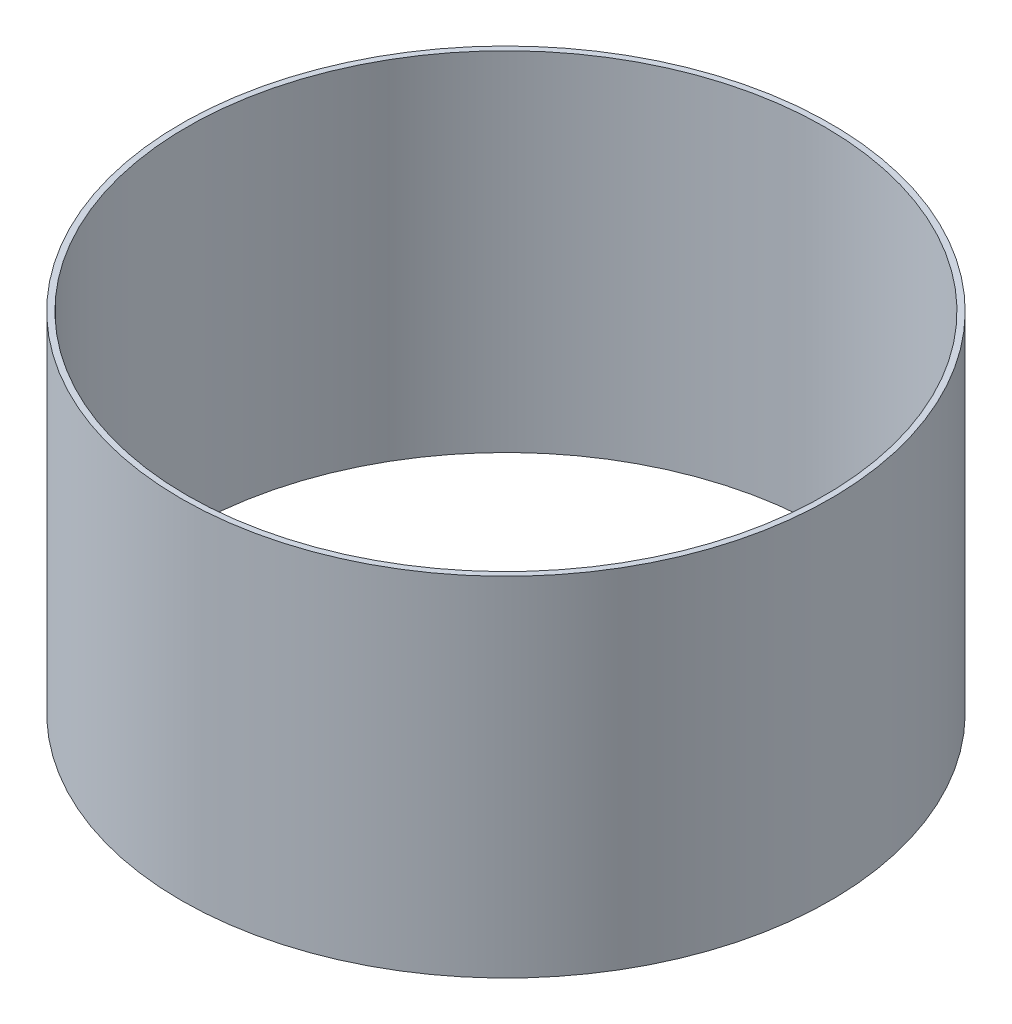
SolidWorks part; units mm, degrees
ref_plane "Front Plane" through (0, 0, 0) normal (0, 0, 1) x (1, 0, 0)
ref_plane "Top Plane" through (0, 0, 0) normal (0, 1, 0) x (1, 0, 0)
ref_plane "Right Plane" through (0, 0, 0) normal (1, 0, 0) x (0, 0, -1)
sketch "Sketch1" plane through (0, 0, 0) normal (0, 1, 0) x (1, 0, 0)
  circle A0 centre (0, 0) radius 280
  circle A1 centre (0, 0) radius 275
  dimension "D1" = 560
  dimension "D2" = 550
extrude "Boss-Extrude1" add sketch "Sketch1" along normal blind 300
